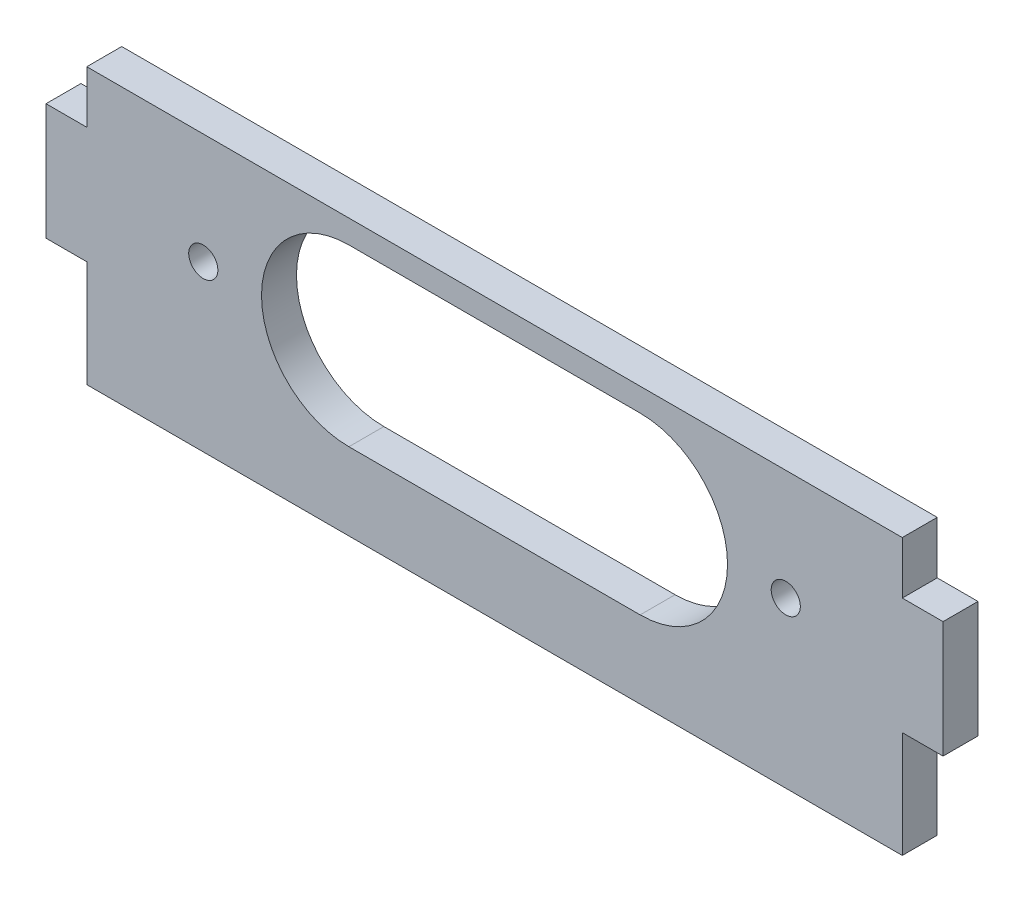
SolidWorks part; units mm, degrees
material "Teak"
ref_plane "Front Plane" through (0, 0, 0) normal (0, 0, 1) x (1, 0, 0)
ref_plane "Top Plane" through (0, 0, 0) normal (0, 1, 0) x (1, 0, 0)
ref_plane "Right Plane" through (0, 0, 0) normal (1, 0, 0) x (0, 0, -1)
sketch "Sketch1" plane through (0, 0, 0) normal (0, 0, 1) x (1, 0, 0)
  point P0 (0, 0)
  line B0 (45, -34) -> (95, -34)
  line B1 (95, -4) -> (45, -4)
  line B2 (140, 0) -> (0, 0)
  line B3 (0, 0) -> (0, -9)
  line B4 (0, -9) -> (-7, -9)
  line B5 (-7, -9) -> (-7, -29)
  line B6 (-7, -29) -> (0, -29)
  line B7 (0, -29) -> (0, -47.27)
  line B8 (0, -47.27) -> (140, -47.27)
  line B9 (140, -47.27) -> (140, -29)
  line B10 (140, -29) -> (147, -29)
  line B11 (147, -29) -> (147, -9)
  line B12 (147, -9) -> (140, -9)
  line B13 (140, -9) -> (140, 0)
  circle B14 centre (120, -19) radius 2.5
  circle B15 centre (20, -19) radius 2.5
  arc B16 (45, -4) -> (45, -34) centre (45, -19) ccw
  arc B17 (95, -34) -> (95, -4) centre (95, -19) ccw
sketch_block_instance "Block1-1"
sketch_block "Block1"
extrude "Boss-Extrude1" add sketch "Sketch1" along normal blind 6
